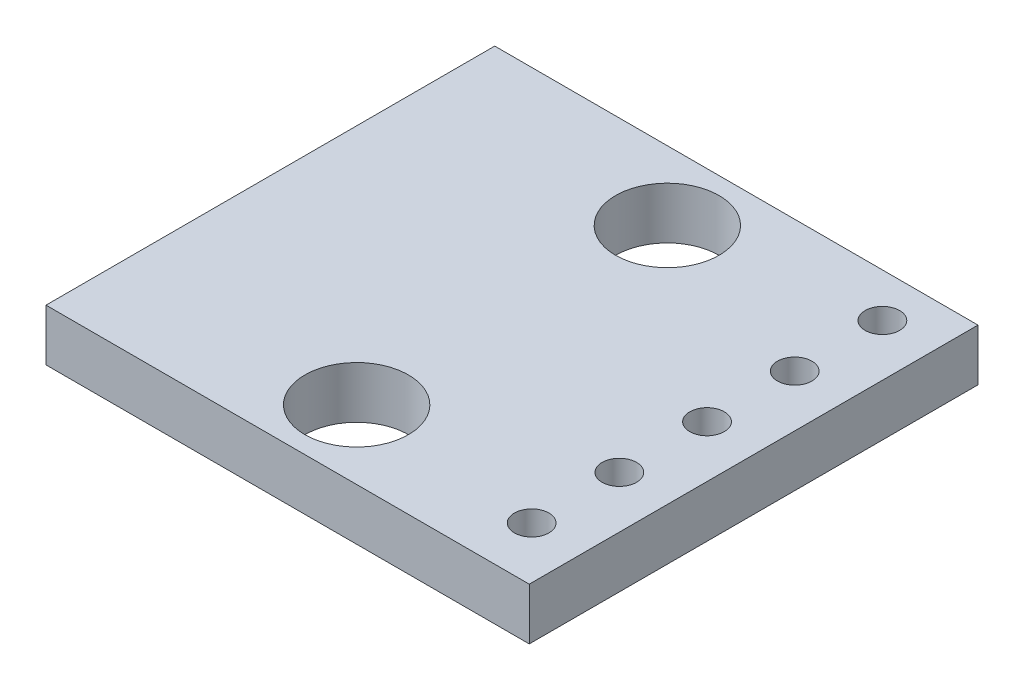
SolidWorks part; units mm, degrees
ref_plane "Front Plane" through (0, 0, 0) normal (0, 0, 1) x (1, 0, 0)
ref_plane "Top Plane" through (0, 0, 0) normal (0, 1, 0) x (1, 0, 0)
ref_plane "Right Plane" through (0, 0, 0) normal (1, 0, 0) x (0, 0, -1)
sketch "Sketch1" plane through (0, 0, 0) normal (0, 1, 0) x (1, 0, 0)
  line L1 (-7, -6.5) -> (7, -6.5)
  line L2 (-7, -6.5) -> (-7, 6.5)
  line L3 (-7, 6.5) -> (7, 6.5)
  line L4 (7, -6.5) -> (7, 6.5)
  line L5 (-7, -6.5) -> (7, 6.5) construction
  line L6 (-7, 6.5) -> (7, -6.5) construction
  point P0 (0, 0)
  dimension "D1" = 13
  dimension "D2" = 14
extrude "Boss-Extrude1" add sketch "Sketch1" along normal blind 1.5
sketch "Sketch2" plane through (0, 1.5, 0) normal (0, 1, 0) x (1, 0, 0)
  line L0 (0, 7.0475) -> (0, -7.2571) construction
  line L1 (-7, 6.5) -> (-7, -6.5) construction
  line L2 (-7, -6.5) -> (7, -6.5) construction
  circle A0 centre (0, 4.5) radius 1.5
  circle A1 centre (0, -4.5) radius 1.5
  circle A2 centre (5.5, -4.93) radius 0.5
  circle A3 centre (5.5, -2.39) radius 0.5
  circle A4 centre (5.5, 0.15) radius 0.5
  circle A5 centre (5.5, 2.69) radius 0.5
  circle A6 centre (5.5, 5.23) radius 0.5
  dimension "D2" = 3
  dimension "D3" = 9
  dimension "D5" = 3
  dimension "D6" = 5.5
  dimension "D7" = 1
  dimension "D9" = 1.57
  dimension "D1" = 7
  dimension "D4" = 4.5
  dimension "D8" = 5
extrude "Cut-Extrude1" cut sketch "Sketch2" against normal blind 1.5
